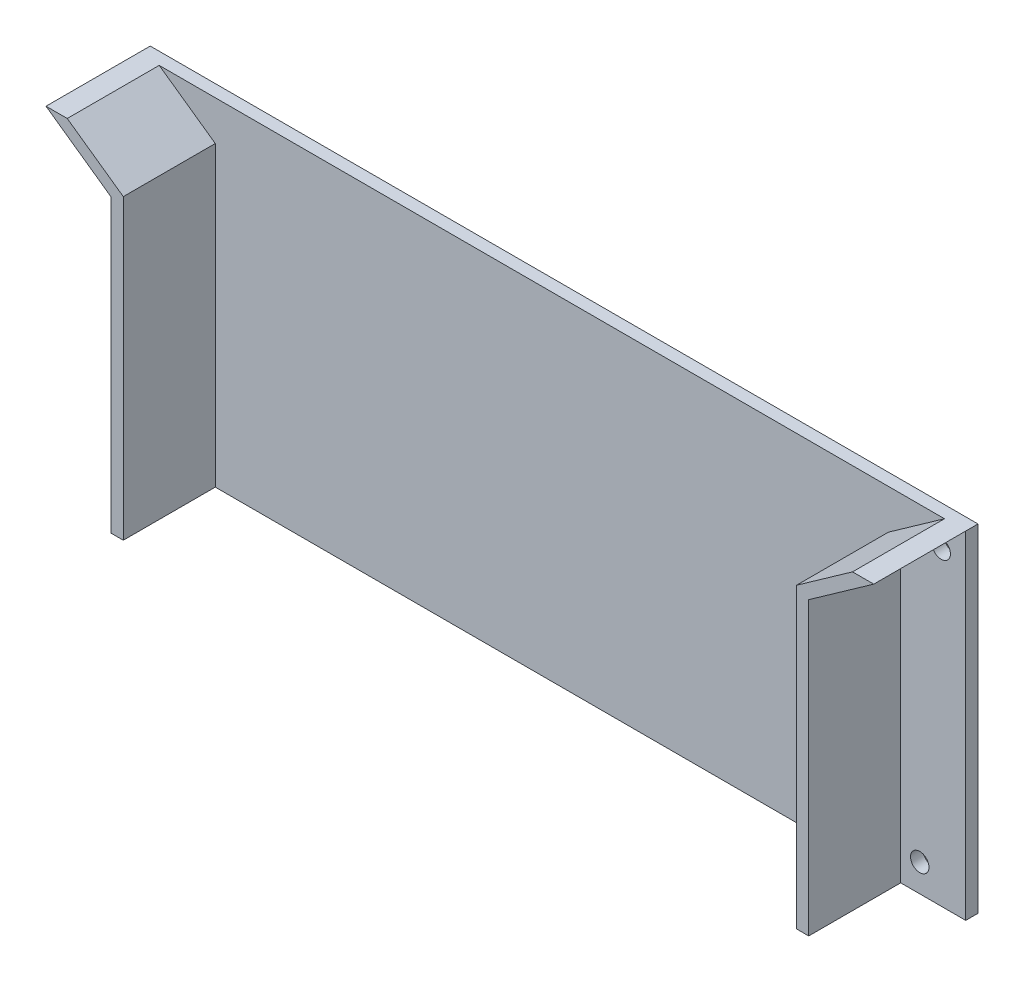
SolidWorks part; units mm, degrees
ref_plane "Front Plane" through (0, 0, 0) normal (0, 0, 1) x (1, 0, 0)
ref_plane "Top Plane" through (0, 0, 0) normal (0, 1, 0) x (1, 0, 0)
ref_plane "Right Plane" through (0, 0, 0) normal (1, 0, 0) x (0, 0, -1)
sketch "Sketch1" plane through (0, 0, 0) normal (0, 0, 1) x (1, 0, 0)
  line L1 (-135, 55) -> (135, 55)
  line L2 (-135, 55) -> (-135, -55)
  line L3 (-135, -55) -> (135, -55)
  line L4 (135, 55) -> (135, -55)
  line L5 (-135, 55) -> (135, -55) construction
  line L6 (-135, -55) -> (135, 55) construction
  point P0 (0, 0)
  dimension "D1" = 270
  dimension "D2" = 110
extrude "Boss-Extrude1" add sketch "Sketch1" along normal blind 4
sketch "Sketch2" plane through (0, 0, 4) normal (0, 0, 1) x (1, 0, 0)
  line L0 (135, 55) -> (-135, 55) construction
  line L1 (-128.0713, 55) -> (-135, 55)
  line L2 (-113.7847, 40) -> (-113.7847, -55)
  line L3 (-113.7847, -55) -> (-109.7847, -55)
  line L4 (-109.7847, 42.0707) -> (-109.7847, -55)
  line L5 (-135, -55) -> (135, -55) construction
  line L6 (0, 0) -> (0, -55) construction
  line L7 (-135, 55) -> (-135, -55) construction
  line L8 (-135, 55) -> (-113.7847, 40)
  line L9 (-128.0713, 55) -> (-109.7847, 42.0707)
  line L10 (-128.0713, 55) -> (-135, 55) construction
  line L11 (-132.6907, 58.2661) -> (-109.7847, 42.0707) construction
  line L12 (128.0713, 55) -> (135, 55) construction
  line L13 (-135, 55) -> (-112.094, 38.8046) construction
  line L14 (128.0713, 55) -> (109.7847, 42.0707)
  line L15 (135, 55) -> (113.7847, 40)
  line L16 (109.7847, 42.0707) -> (109.7847, -55)
  line L17 (113.7847, -55) -> (109.7847, -55)
  line L18 (113.7847, 40) -> (113.7847, -55)
  line L19 (128.0713, 55) -> (135, 55)
  dimension "D1" = 4
  dimension "D2" = 21.2153
  dimension "D4" = 15
  dimension "D3" = 4
extrude "Boss-Extrude2" add sketch "Sketch2" along normal blind 30
sketch "Sketch3" plane through (0, 0, 4) normal (0, 0, 1) x (1, 0, 0)
  circle A0 centre (-120, -46) radius 3 construction
  circle A1 centre (120, -46) radius 3 construction
  circle A2 centre (127, 46) radius 3 construction
  circle A3 centre (-127, 46) radius 3 construction
  circle A4 centre (-120, -46) radius 3
  circle A5 centre (120, -46) radius 3
  circle A6 centre (127, 46) radius 3
  circle A7 centre (-127, 46) radius 3
extrude "Cut-Extrude1" cut sketch "Sketch3" against normal blind 30
